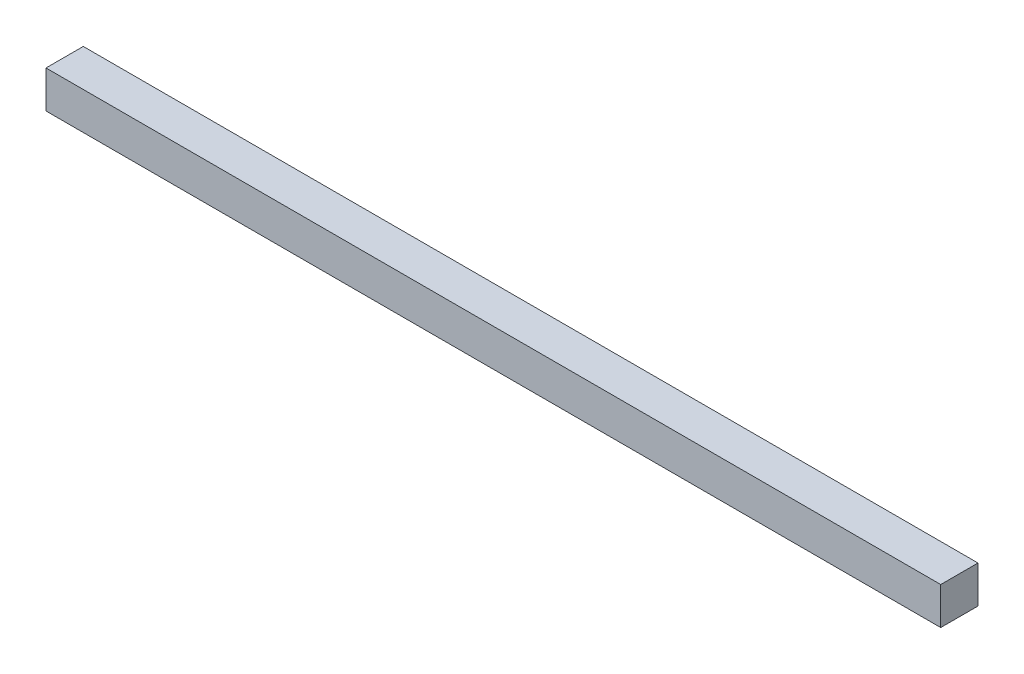
SolidWorks part; units mm, degrees
ref_plane "Front Plane" through (0, 0, 0) normal (0, 0, 1) x (1, 0, 0)
ref_plane "Top Plane" through (0, 0, 0) normal (0, 1, 0) x (1, 0, 0)
ref_plane "Right Plane" through (0, 0, 0) normal (1, 0, 0) x (0, 0, -1)
sketch "Sketch1" plane through (0, 0, 0) normal (0, 1, 0) x (1, 0, 0)
  line L1 (0, 0) -> (914.4, 0)
  line L2 (0, 0) -> (0, 38.1)
  line L3 (0, 38.1) -> (914.4, 38.1)
  line L4 (914.4, 0) -> (914.4, 38.1)
  dimension "D1" = 914.4
  dimension "D2" = 38.1
extrude "Extrude1" add sketch "Sketch1" along normal blind 38.1
